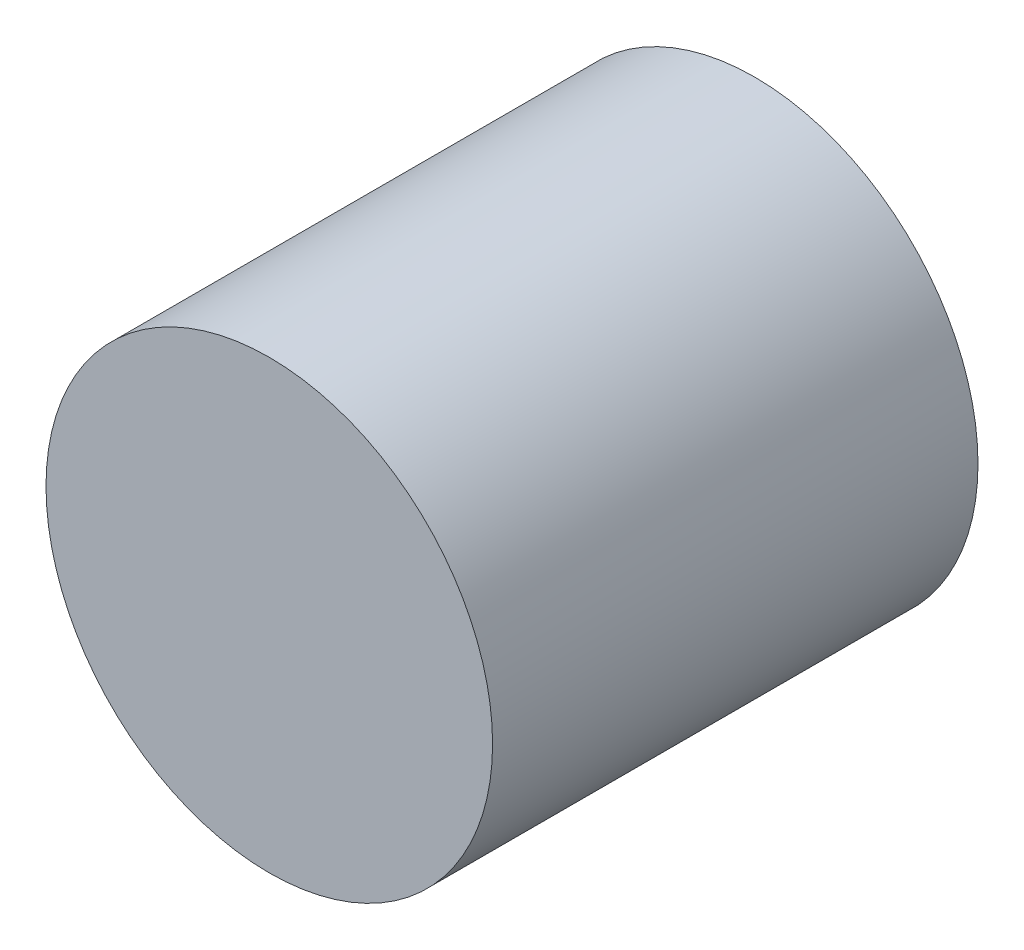
SolidWorks part; units mm, degrees
ref_plane "Front Plane" through (0, 0, 0) normal (0, 0, 1) x (1, 0, 0)
ref_plane "Top Plane" through (0, 0, 0) normal (0, 1, 0) x (1, 0, 0)
ref_plane "Right Plane" through (0, 0, 0) normal (1, 0, 0) x (0, 0, -1)
sketch "Sketch1" plane through (0, 0, 0) normal (0, 0, 1) x (1, 0, 0)
  circle A0 centre (0, 0) radius 2.3
  dimension "D1" = 4.6
extrude "Boss-Extrude1" add sketch "Sketch1" along normal blind 5
